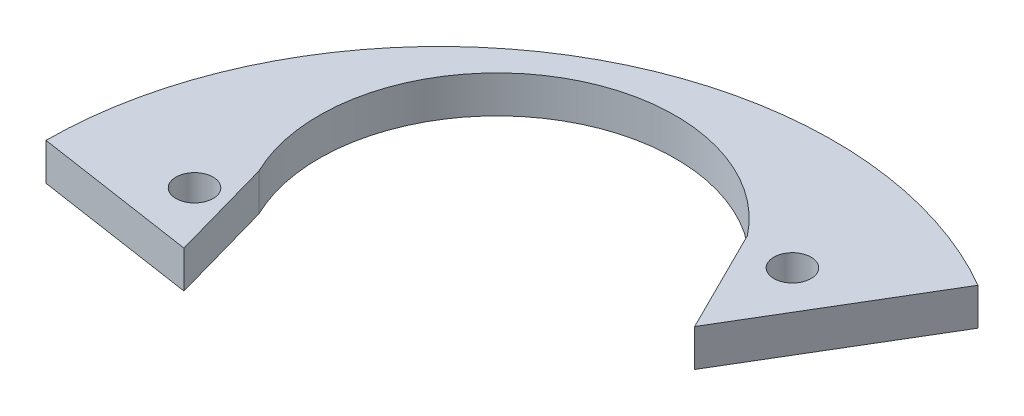
SolidWorks part; units mm, degrees
ref_plane "Front Plane" through (0, 0, 0) normal (0, 0, 1) x (1, 0, 0)
ref_plane "Top Plane" through (0, 0, 0) normal (0, 1, 0) x (1, 0, 0)
ref_plane "Right Plane" through (0, 0, 0) normal (1, 0, 0) x (0, 0, -1)
sketch "Sketch1" plane through (0, 0, 0) normal (0, 1, 0) x (1, 0, 0)
  line L0 (2.3104, 4.0256) -> (6.5305, -4.4526)
  line L1 (6.5305, -4.4526) -> (15.0717, 9.8576)
  line L2 (-32.6237, -17.6024) -> (-19.5377, -19.5651)
  line L3 (-19.5377, -19.5651) -> (-21.9226, -11.0854)
  arc A0 (15.0717, 9.8576) -> (-32.6237, -17.6024) centre (-0.8438, -17.6499) ccw
  arc A1 (2.3104, 4.0256) -> (-21.8492, -11.2622) centre (-8.982, -4.8626) ccw
  circle A2 centre (6.3772, 3.5908) radius 1.5
  circle A3 centre (-23.3218, -14.9286) radius 1.5
  dimension "D2" = 31.7799
  dimension "D6" = 3
  dimension "D7" = 3
  dimension "D8" = 14.3708
  dimension "D1" = 13.086
  dimension "D3" = 8.8088
  dimension "D4" = 16.6653
  dimension "D5" = 9.4704
extrude "Boss-Extrude1" add sketch "Sketch1" along normal blind 3 contours A1 L0 L1 A0 L2 L3 A3 A2
